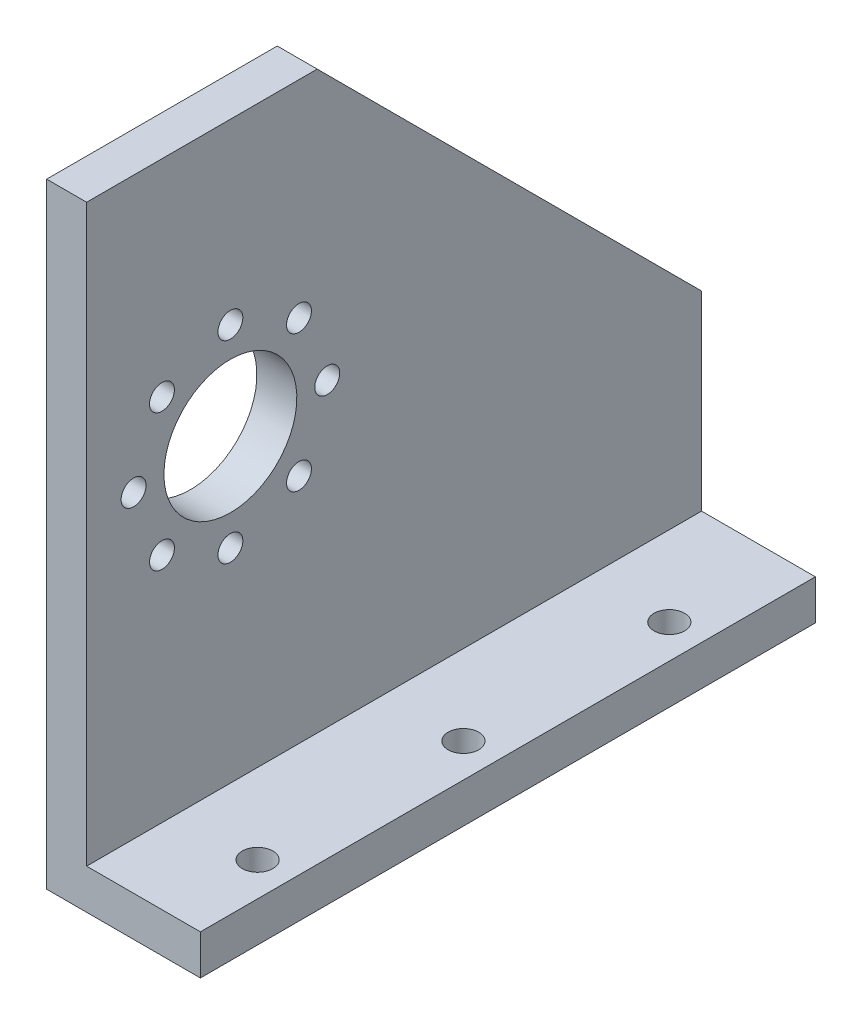
SolidWorks part; units mm, degrees
material "6061-T6 (SS)"
ref_plane "Front Plane" through (0, 0, 0) normal (0, 0, 1) x (1, 0, 0)
ref_plane "Top Plane" through (0, 0, 0) normal (0, 1, 0) x (1, 0, 0)
ref_plane "Right Plane" through (0, 0, 0) normal (1, 0, 0) x (0, 0, -1)
sketch "Sketch4" plane through (0, 0, 0) normal (0, 0, 1) x (1, 0, 0)
  line L0 (0, 0) -> (0, 50.8)
  line L1 (0, 50.8) -> (3.302, 50.8)
  line L2 (3.302, 50.8) -> (3.302, 3.302)
  line L3 (3.302, 3.302) -> (12.7, 3.302)
  line L4 (12.7, 3.302) -> (12.7, 0)
  line L5 (12.7, 0) -> (0, 0)
  dimension "D1" = 50.8
  dimension "D2" = 3.302
  dimension "D3" = 3.302
  dimension "D4" = 12.7
extrude "Boss-Extrude1" add sketch "Sketch4" along normal blind 50.8
hole_wizard "#39 (0.0995) Diameter Hole1" positions "Sketch5" profile "Sketch6" hole size "#39" standard "ANSI Inch" end condition through all
sketch "Sketch5" plane through (0, 0, 0) normal (0, -1, 0) x (-1, 0, 0)
  point P0 (-9.9087, -43.2834)
  point P3 (-9.9087, -26.2817)
  point P5 (-9.9087, -9.2701)
sketch "Sketch6" plane through (9.9087, 0, 43.2834) normal (1, 0, 0) x (0, 0, -1)
  line L0 (0, 0) -> (0, 50.8)
  line L1 (0, 50.8) -> (1.2636, 50.8)
  line L2 (1.2636, 50.8) -> (1.2636, 0)
  line L5 (1.2636, 0) -> (0, 0)
  line L11 (0, -6.35) -> (0, 107.95) construction
  dimension "Thru Hole Dia." = 2.5273
  dimension "Thru Hole Depth" = 50.8
hole_wizard "#46 (0.081) Diameter Hole1" positions "Sketch7" profile "Sketch8" hole size "#46" standard "ANSI Inch" end condition through all
sketch "Sketch7" plane through (0, 0, 0) normal (-1, 0, 0) x (0, 0, 1)
  point P0 (38.9241, 20.1327)
  point P3 (33.2567, 22.4501)
  point P5 (30.9241, 28.1327)
  point P8 (33.2567, 33.7546)
  point P10 (38.9241, 36.0968)
  point P12 (44.5766, 33.7637)
  point P14 (46.9217, 28.1016)
  point P16 (44.5766, 22.4501)
sketch "Sketch8" plane through (0, 20.1327, 38.9241) normal (0, 1, 0) x (0, 0, 1)
  line L0 (0, 0) -> (0, 12.7)
  line L1 (0, 12.7) -> (1.0287, 12.7)
  line L2 (1.0287, 12.7) -> (1.0287, 0)
  line L5 (1.0287, 0) -> (0, 0)
  line L11 (0, -6.35) -> (0, 107.95) construction
  dimension "Thru Hole Dia." = 2.0574
  dimension "Thru Hole Depth" = 12.7
sketch "Sketch9" plane through (0, 0, 0) normal (-1, 0, 0) x (0, 0, 1)
  line L0 (0, 19.05) -> (31.75, 50.8)
  line L1 (0, 50.8) -> (0, 0) construction
  line L2 (50.8, 50.8) -> (0, 50.8) construction
  line L5 (0, 50.8) -> (0, 19.05)
  line L6 (0, 50.8) -> (31.75, 50.8)
  circle A0 centre (38.9241, 28.1327) radius 5.4899
  dimension "D1" = 31.75
  dimension "D3" = 10.9797
  dimension "D2" = 31.75
extrude "Cut-Extrude1" cut sketch "Sketch9" against normal through all
